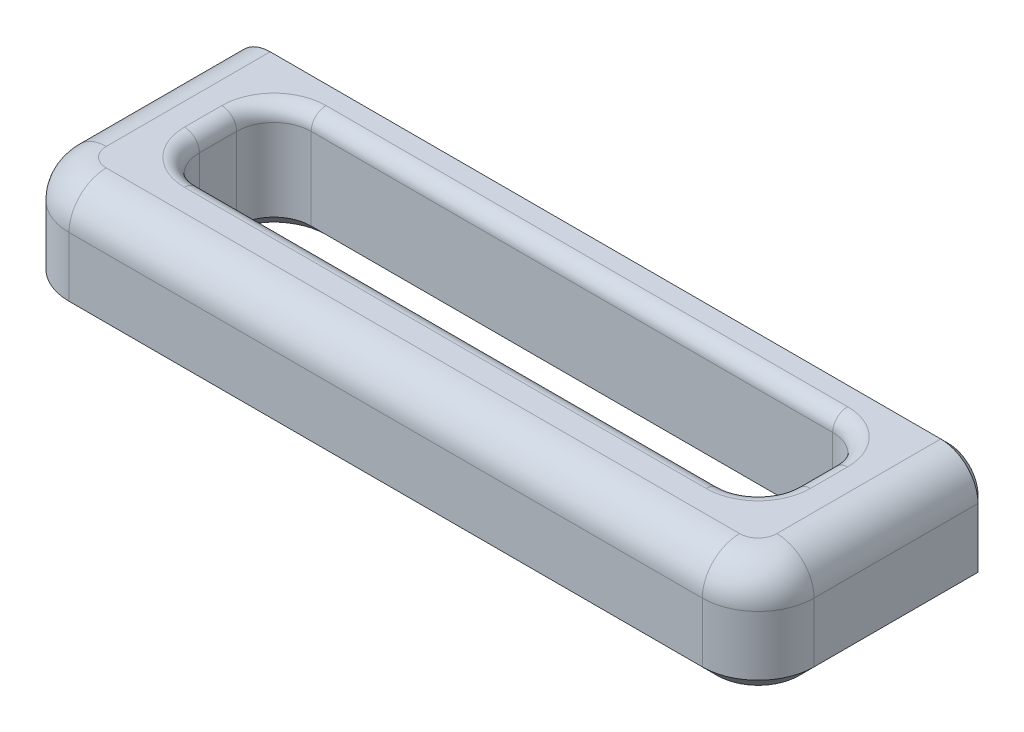
SolidWorks part; units mm, degrees
ref_plane "前视基准面" through (0, 0, 0) normal (0, 0, 1) x (1, 0, 0)
ref_plane "上视基准面" through (0, 0, 0) normal (0, 1, 0) x (1, 0, 0)
ref_plane "右视基准面" through (0, 0, 0) normal (1, 0, 0) x (0, 0, -1)
other "Configuration Table"
sketch "草图1" plane through (0, 0, 0) normal (0, 1, 0) x (1, 0, 0)
  line L1 (0, 0) -> (20, 0)
  line L2 (0, 0) -> (0, 6.1)
  line L3 (0, 6.1) -> (20, 6.1)
  line L4 (20, 0) -> (20, 6.1)
  dimension "D1" = 6.1
  dimension "D2" = 20
extrude "凸台-拉伸1" add sketch "草图1" along normal blind 3
sketch "草图2" plane through (0, 3, 0) normal (0, 1, 0) x (1, 0, 0)
  line L1 (2, 5) -> (18, 5)
  line L2 (2, 5) -> (2, 2)
  line L3 (2, 2) -> (18, 2)
  line L4 (18, 5) -> (18, 2)
  line L5 (20, 6.1) -> (0, 6.1) construction
  point P4 (10, 5)
  point P7 (10, 6.1)
  dimension "D1" = 3
  dimension "D2" = 0
  dimension "D3" = 16
  dimension "D4" = 1.1
extrude "切除-拉伸1" cut sketch "草图2" against normal blind 3
fillet "圆角1" radius 1 4 edges at (2, 1.5, -5) (18, 1.5, -5) (18, 1.5, -2) (2, 1.5, -2)
fillet "圆角2" radius 1.5 2 edges at (0, 1.5, 0) (20, 1.5, 0)
fillet "圆角3" radius 1 5 edges at (0, 3, -3.8) (0.4393, 3, -0.4393) (20, 3, -3.8) (19.5607, 3, -0.4393) (10, 3, 0)
chamfer "倒角1" distance 0.4 angle 45 14 edges at (19.5607, 0, -0.4393) (20, 0, -3.8) (10, 0, -6.1) (0, 0, -3.8) (0.4393, 0, -0.4393) (10, 0, 0) (17.7071, 0, -4.7071) (18, 0, -3.5) (17.7071, 0, -2.2929) (10, 0, -2) (2.2929, 0, -2.2929) (2, 0, -3.5) (2.2929, 0, -4.7071) (10, 0, -5)
fillet "圆角4" radius 0.4 8 edges at (2.2929, 3, -2.2929) (2, 3, -3.5) (2.2929, 3, -4.7071) (10, 3, -5) (17.7071, 3, -4.7071) (18, 3, -3.5) (17.7071, 3, -2.2929) (10, 3, -2)
chamfer "倒角2" distance 0.2 angle 45 8 edges at (19.8, 0.2, -6.1) (20, 1.2, -6.1) (19.7071, 2.7071, -6.1) (10, 3, -6.1) (0.2929, 2.7071, -6.1) (0, 1.2, -6.1) (0.2, 0.2, -6.1) (10, 0, -6.1)
